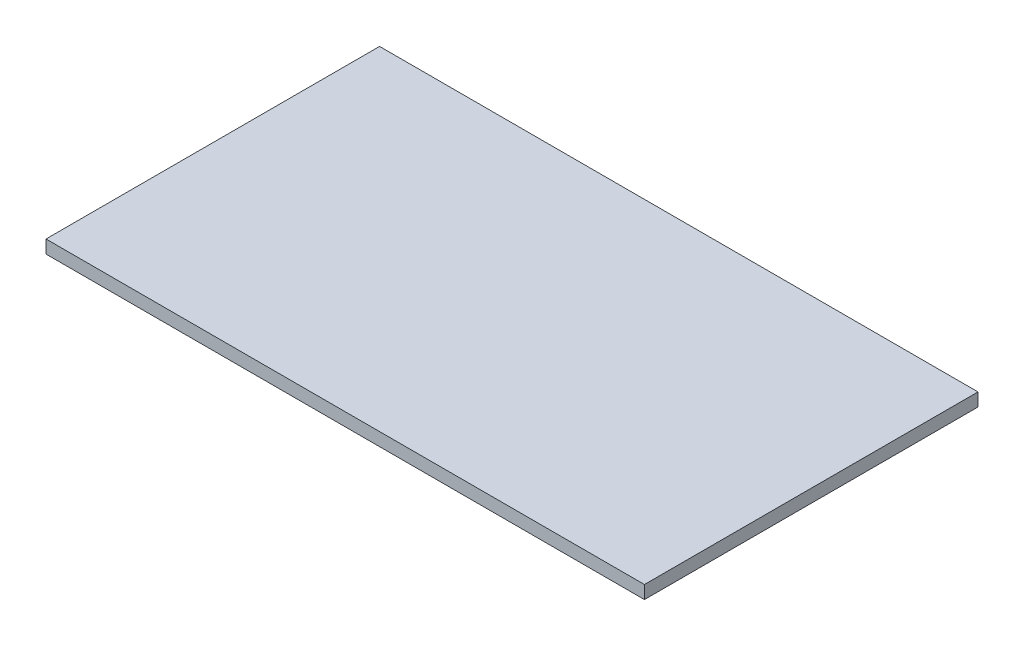
SolidWorks part; units mm, degrees
material "有机玻璃 (TM) GS 丙烯酸铸钣"
ref_plane "前视基准面" through (0, 0, 0) normal (0, 0, 1) x (1, 0, 0)
ref_plane "上视基准面" through (0, 0, 0) normal (0, 1, 0) x (1, 0, 0)
ref_plane "右视基准面" through (0, 0, 0) normal (1, 0, 0) x (0, 0, -1)
sketch "草图1" plane through (0, 0, 0) normal (0, 1, 0) x (1, 0, 0)
  line L1 (0, 0) -> (183, 0)
  line L2 (0, 0) -> (0, 102)
  line L3 (0, 102) -> (183, 102)
  line L4 (183, 0) -> (183, 102)
  dimension "D1" = 183
  dimension "D2" = 102
extrude "凸台-拉伸1" add sketch "草图1" along normal blind 4
